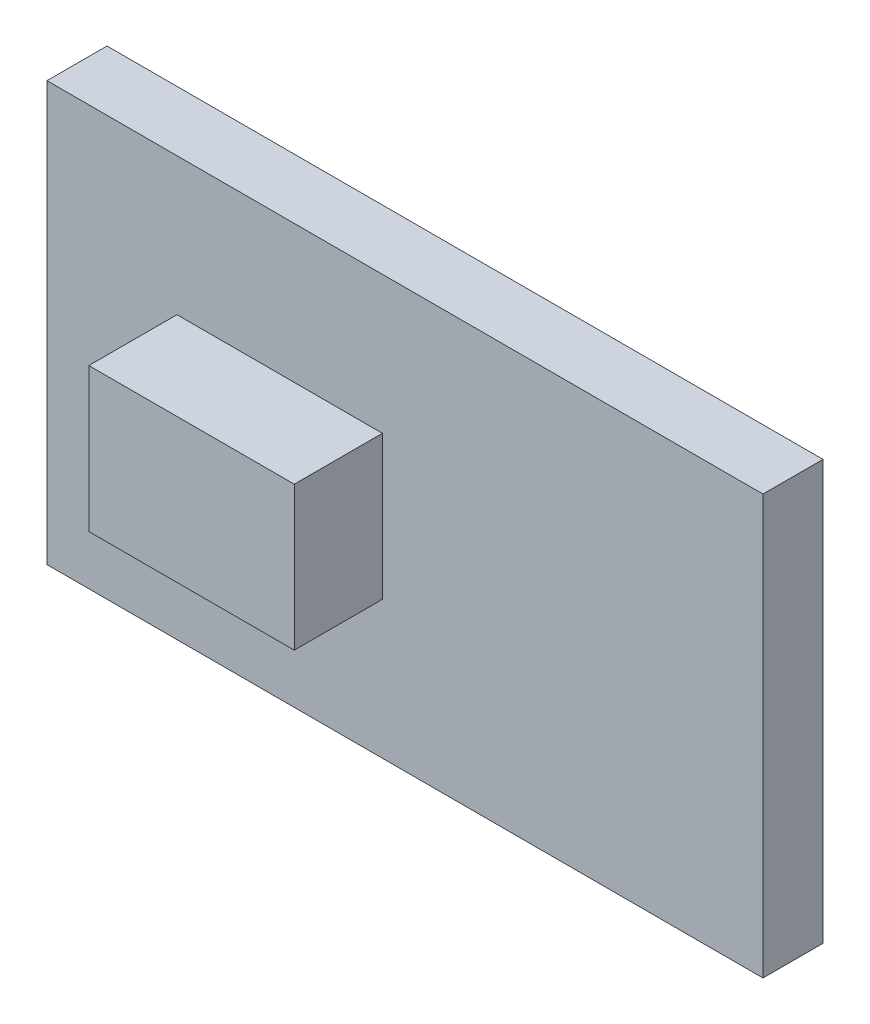
SolidWorks part; units mm, degrees
ref_plane "Plan de face" through (0, 0, 0) normal (0, 0, 1) x (1, 0, 0)
ref_plane "Plan de dessus" through (0, 0, 0) normal (0, 1, 0) x (1, 0, 0)
ref_plane "Plan de droite" through (0, 0, 0) normal (1, 0, 0) x (0, 0, -1)
sketch "Esquisse1" plane through (0, 0, 0) normal (0, 0, 1) x (1, 0, 0)
  line L0 (-29.2958, 7.61) -> (-16.2958, 7.61)
  line L1 (-16.2958, 7.61) -> (-16.2958, 0)
  line L2 (-16.2958, 0) -> (-29.2958, 0)
  line L3 (-29.2958, 0) -> (-29.2958, 7.61)
  dimension "D1" = 13
  dimension "D2" = 7.61
extrude "Boss.-Extru.3" add sketch "Esquisse1" along normal blind 1.09
sketch "Esquisse4" plane through (0, 0, 1.09) normal (0, 0, 1) x (1, 0, 0)
  line L0 (-26.9358, 5.11) -> (-23.2058, 5.11)
  line L1 (-23.2058, 5.11) -> (-23.2058, 2.5)
  line L2 (-23.2058, 2.5) -> (-26.9358, 2.5)
  line L3 (-26.9358, 2.5) -> (-26.9358, 5.11)
  line L4 (-29.2958, 7.61) -> (-29.2958, 0) construction
  line L5 (-16.2958, 0) -> (-16.2958, 7.61) construction
  line L6 (-16.2958, 7.61) -> (-29.2958, 7.61) construction
  line L7 (-29.2958, 0) -> (-16.2958, 0) construction
  dimension "D1" = 2.36
  dimension "D2" = 6.91
  dimension "D3" = 2.5
  dimension "D4" = 2.5
  dimension "D5" = 2.61
  dimension "D6" = 3.73
extrude "Boss.-Extru.4" add sketch "Esquisse4" along normal blind 1.6
